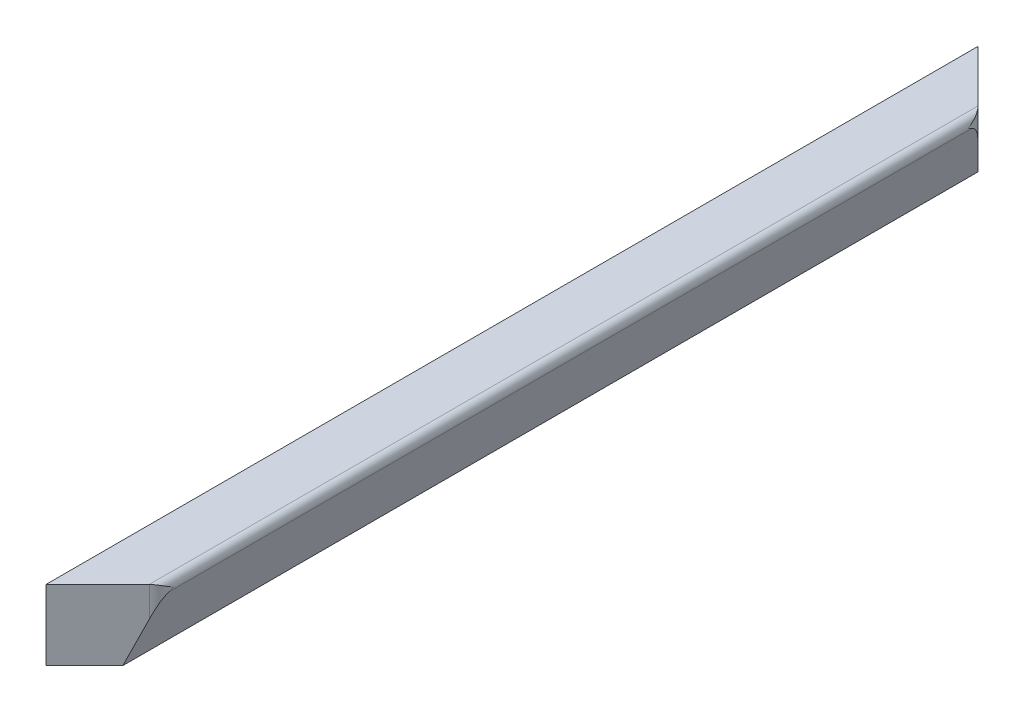
SolidWorks part; units mm, degrees
ref_plane "Alzado" through (0, 0, 0) normal (0, 0, 1) x (1, 0, 0)
ref_plane "Planta" through (0, 0, 0) normal (0, 1, 0) x (1, 0, 0)
ref_plane "Vista lateral" through (0, 0, 0) normal (1, 0, 0) x (0, 0, -1)
sketch "Croquis1" plane through (0, 0, 0) normal (0, 0, 1) x (1, 0, 0)
  line L0 (-24.95, 2.0659) -> (-24.95, 4.9959)
  line L1 (-24.95, 4.9959) -> (-22.8, 4.9959)
  line L3 (-24.95, 4.6959) -> (-22.5, 4.6959) construction
  line L4 (-24.95, 2.0659) -> (-23.35, 2.0659)
  line L5 (-23.35, 2.0659) -> (-22.515, 4.6021)
  arc A0 (-22.8, 4.9959) -> (-22.515, 4.6021) centre (-22.8, 4.6959) cw
  point P2 (-23.8326, 2.0659)
  dimension "D2" = 0.3
  dimension "D1" = 2.45
  dimension "D3" = 2.93
  dimension "D4" = 0.85
extrude "Saliente-Extruir1" add sketch "Croquis1" against normal blind 38.8283
sketch "Croquis3" plane through (0, 4.9959, 0) normal (0, 1, 0) x (1, 0, 0)
  line L0 (-24.95, 38.8283) -> (-22.7929, 36.6712)
  line L1 (-22.5, 0) -> (-22.5, 38.8283) construction
  line L2 (-22.5, 0) -> (-22.5, 38.8283) construction
  line L3 (-22.5, 35.9641) -> (-22.5, 2.8642)
  line L4 (-22.7929, 2.1571) -> (-24.95, 0)
  line L5 (-24.95, 0) -> (-24.95, -1.3539)
  line L6 (-24.95, -1.3539) -> (-20.6762, -1.3539)
  line L7 (-20.6762, -1.3539) -> (-20.6762, 40.3622)
  line L8 (-20.6762, 40.3622) -> (-24.95, 40.3622)
  line L9 (-24.95, 40.3622) -> (-24.95, 38.8283)
  line L10 (-24.95, 38.8283) -> (-24.95, 0) construction
  arc A0 (-22.7929, 2.1571) -> (-22.5, 2.8642) centre (-23.5, 2.8642) ccw
  arc A1 (-22.5, 35.9641) -> (-22.7929, 36.6712) centre (-23.5, 35.9641) ccw
  point P16 (-22.5, 2.45)
  point P19 (-22.5, 36.3783)
  dimension "D3" = 1
  dimension "D1" = 45
  dimension "D2" = 45
extrude "Cortar-Extruir1" cut sketch "Croquis3" against normal up to surface (2.93 mm away) up to face at (-24.15, 2.0659, -19.4142)
